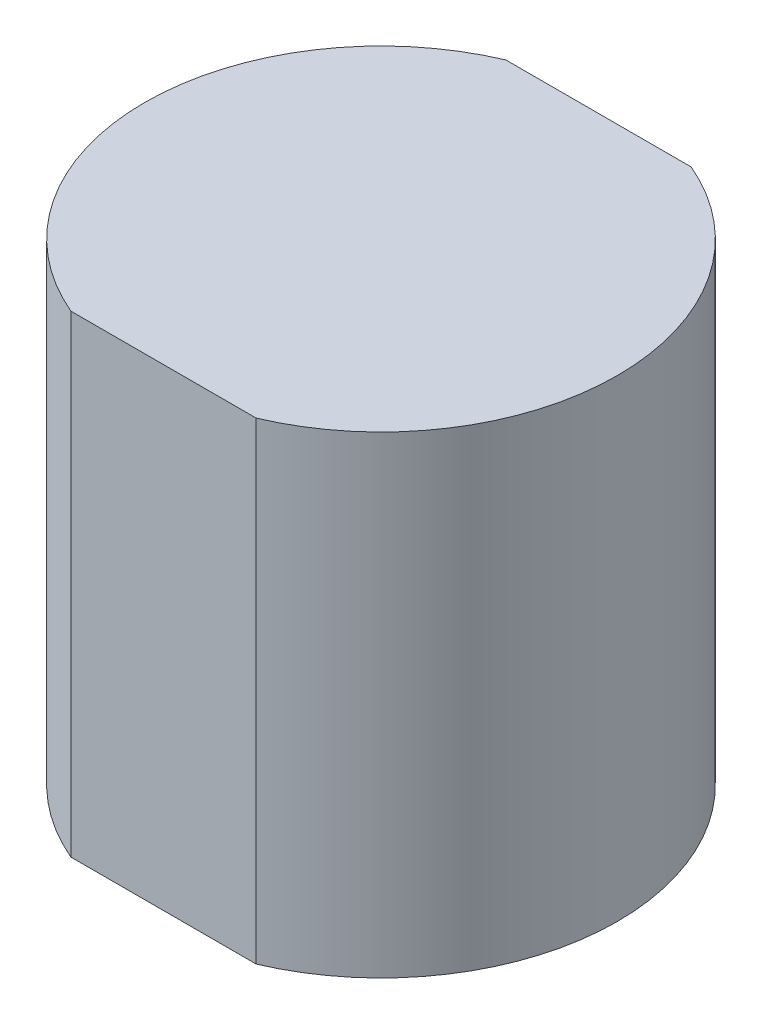
SolidWorks part; units mm, degrees
ref_plane "前视基准面" through (0, 0, 0) normal (0, 0, 1) x (1, 0, 0)
ref_plane "上视基准面" through (0, 0, 0) normal (0, 1, 0) x (1, 0, 0)
ref_plane "右视基准面" through (0, 0, 0) normal (1, 0, 0) x (0, 0, -1)
sketch "草图1" plane through (0, 0, 0) normal (0, 1, 0) x (1, 0, 0)
  circle A0 centre (0, 0) radius 250
extrude "凸台-拉伸1" add sketch "草图1" along normal blind 500
sketch "草图2" plane through (0, 0, 0) normal (0, -1, 0) x (1, 0, 0)
  line L1 (273.2532, -230) -> (-273.2532, -230)
  line L2 (273.2532, -230) -> (273.2532, 230)
  line L3 (273.2532, 230) -> (-273.2532, 230)
  line L4 (-273.2532, -230) -> (-273.2532, 230)
  line L5 (273.2532, -230) -> (-273.2532, 230) construction
  line L6 (273.2532, 230) -> (-273.2532, -230) construction
  point P0 (0, 0)
  dimension "D1" = 460
extrude "切除-拉伸1" cut sketch "草图2" against normal blind 599 flip side to cut
